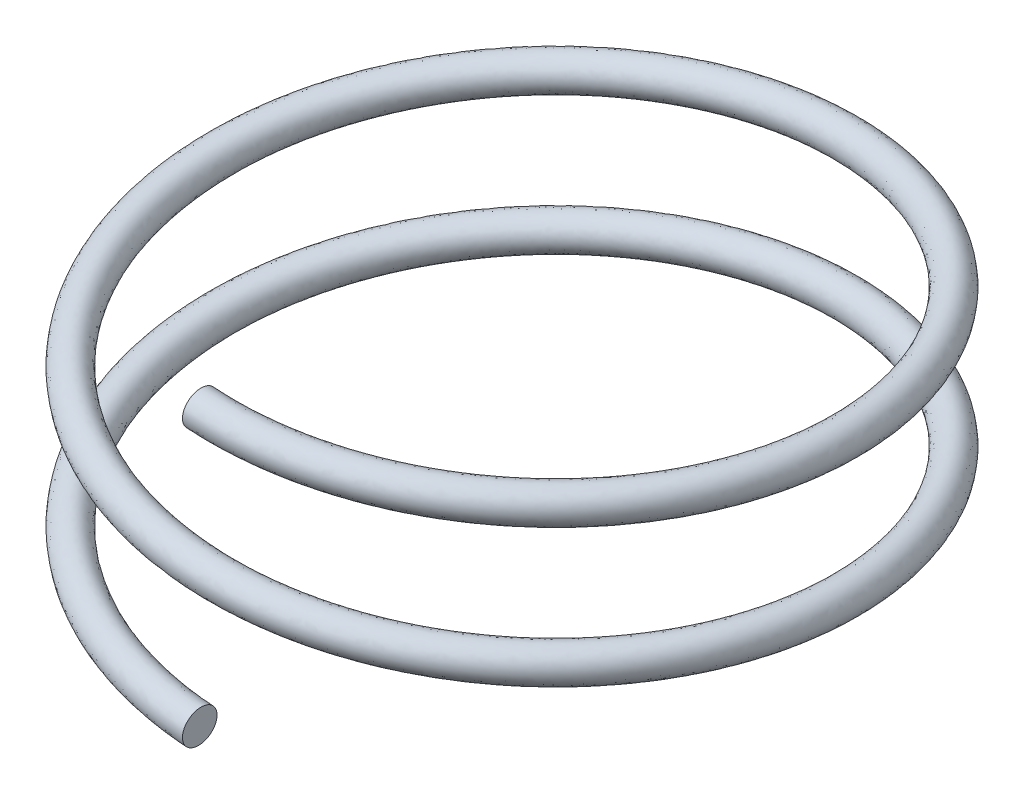
SolidWorks part; units mm, degrees
material "Сталь 3 ГОСТ 535-88"
ref_plane "Спереди" through (0, 0, 0) normal (0, 0, 1) x (1, 0, 0)
ref_plane "Сверху" through (0, 0, 0) normal (0, 1, 0) x (1, 0, 0)
ref_plane "Справа" through (0, 0, 0) normal (1, 0, 0) x (0, 0, -1)
sketch "Эскиз2" plane through (0, 0, 0) normal (0, 1, 0) x (1, 0, 0)
  circle A0 centre (0, 0) radius 45
  dimension "D1" = 90
curve "Спираль1" pitch 20 height 40 turns 2
ref_plane "Плоскость1" through (0, 0, 45) normal (-0.9975, 0.0706, 0) x (0, 0, 1)
sketch "Эскиз3" plane through (0, 0, 45) normal (-0.9975, 0.0706, 0) x (0, 0, 1)
  circle A0 centre (0.197, 0) radius 2.5
  dimension "D1" = 5
sweep "По траектории1" add profiles "Эскиз3" path "Спираль1"
sketch "Эскиз4" plane through (0, 0, 0) normal (0, 1, 0) x (1, 0, 0)
  line L1 (-63.7664, 67.7576) -> (70.4263, 67.7576)
  line L2 (-63.7664, 67.7576) -> (-63.7664, -67.7576)
  line L3 (-63.7664, -67.7576) -> (70.4263, -67.7576)
  line L4 (70.4263, 67.7576) -> (70.4263, -67.7576)
  line L5 (3.33, -67.7576) -> (3.33, 67.7576) construction
  line L6 (-63.7664, 0) -> (70.4263, 0) construction
  point P0 (3.33, 0)
extrude "Вырез-Вытянуть1" [suppressed] cut sketch "Эскиз4" against normal through all
ref_plane "Плоскость2" through (0, 40, 0) normal (0, 1, 0) x (1, 0, 0)
sketch "Эскиз5" plane through (0, 40, 0) normal (0, 1, 0) x (1, 0, 0)
  line L4 (70.4263, 67.7576) -> (-63.7664, 67.7576)
  line L5 (-63.7664, 67.7576) -> (-63.7664, -67.7576)
  line L6 (-63.7664, -67.7576) -> (70.4263, -67.7576)
  line L7 (70.4263, -67.7576) -> (70.4263, 67.7576)
  line L8 (70.4263, 67.7576) -> (-63.7664, 67.7576)
  line L9 (-63.7664, 67.7576) -> (-63.7664, -67.7576)
  line L10 (-63.7664, -67.7576) -> (70.4263, -67.7576)
  line L11 (70.4263, -67.7576) -> (70.4263, 67.7576)
  dimension "D1" = 0
extrude "Вырез-Вытянуть2" [suppressed] cut sketch "Эскиз5" along normal through all
